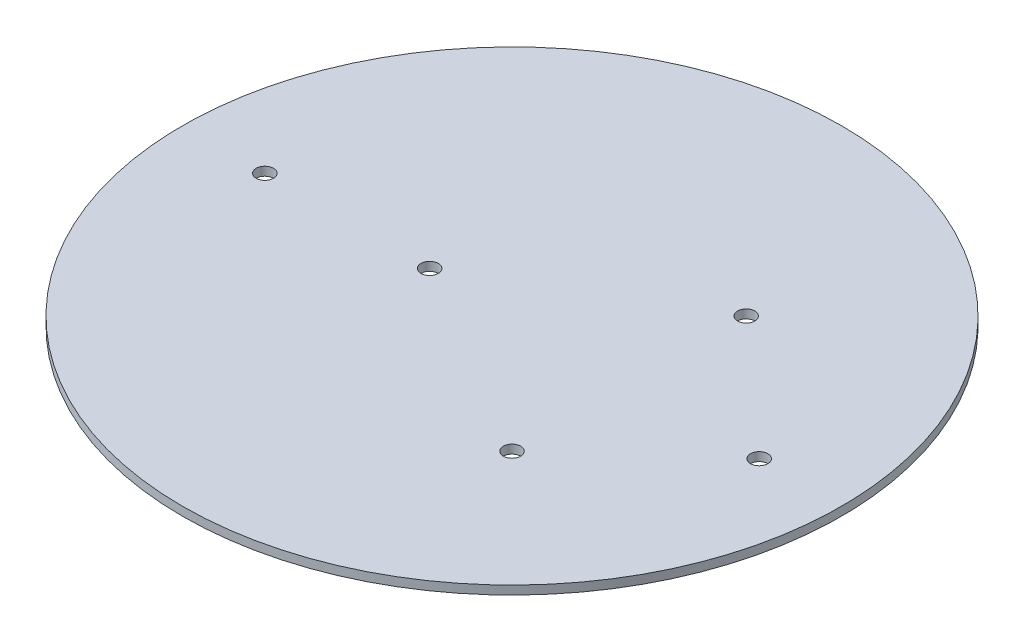
SolidWorks part; units mm, degrees
ref_plane "Front Plane" through (0, 0, 0) normal (0, 0, 1) x (1, 0, 0)
ref_plane "Top Plane" through (0, 0, 0) normal (0, 1, 0) x (1, 0, 0)
ref_plane "Right Plane" through (0, 0, 0) normal (1, 0, 0) x (0, 0, -1)
sketch "Sketch1" plane through (0, 0, 0) normal (0, 1, 0) x (1, 0, 0)
  line L0 (-28.5, 0) -> (28.5, 0) construction
  line L1 (13.5, 13.5) -> (13.5, -13.5) construction
  circle A0 centre (0, 0) radius 38
  circle A1 centre (28.5, 0) radius 1
  circle A2 centre (-28.5, 0) radius 1
  circle A3 centre (13.5, 13.5) radius 1
  circle A4 centre (13.5, -13.5) radius 1
  circle A5 centre (-28.5, 0) radius 6.25 construction
  circle A6 centre (13.5, 13.5) radius 12.5 construction
  circle A7 centre (13.5, -13.5) radius 12.5 construction
  circle A8 centre (28.5, 0) radius 6.25 construction
  circle A9 centre (-9.5, 0) radius 1
  circle A10 centre (-9.5, 0) radius 12.5 construction
  point P2 (13.5, 0)
  point P11 (0, 0)
  dimension "D1" = 76
  dimension "D3" = 2
  dimension "D4" = 13.5
  dimension "D5" = 2
  dimension "D6" = 12.5
  dimension "D7" = 25
  dimension "D9" = 2
  dimension "D10" = 25
  dimension "D2" = 57
  dimension "D8" = 13.5
  dimension "D11" = 9.5
extrude "Boss-Extrude1" add sketch "Sketch1" against normal blind 1
